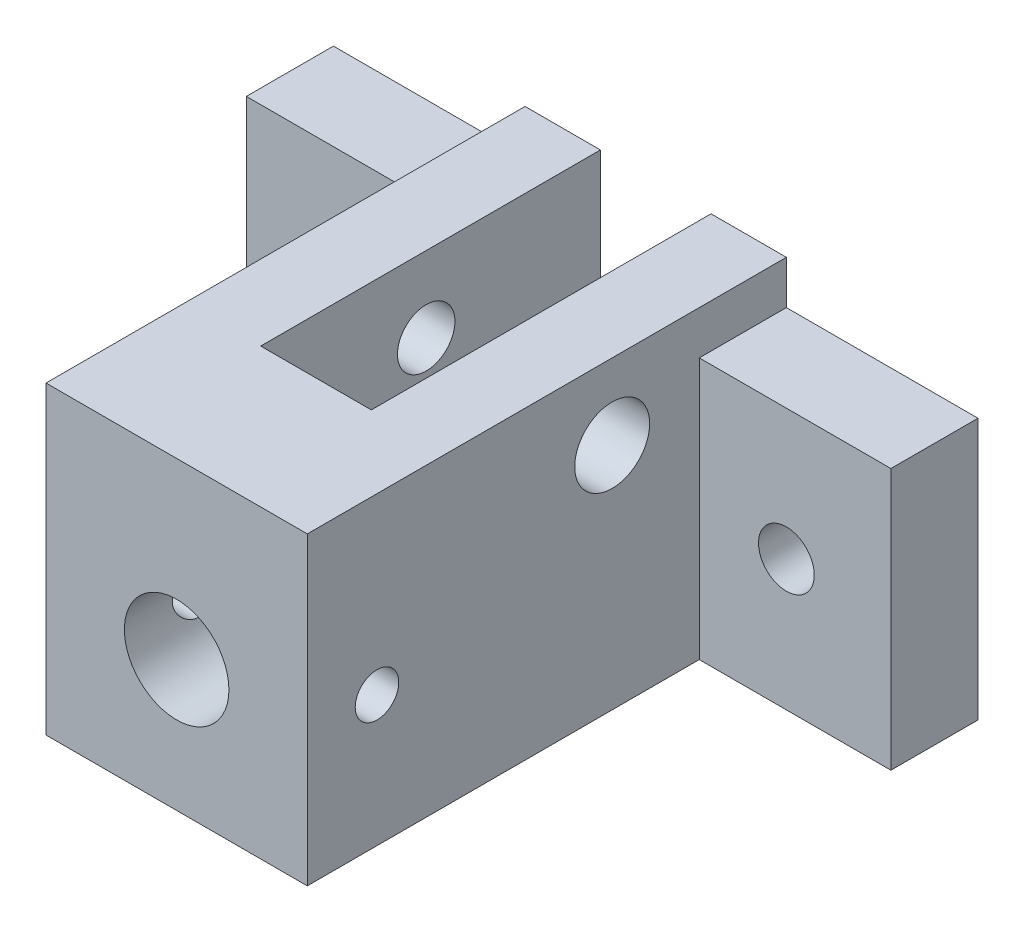
SolidWorks part; units mm, degrees
material "6061-T6 (SS)"
ref_plane "Front Plane" through (0, 0, 0) normal (0, 0, 1) x (1, 0, 0)
ref_plane "Top Plane" through (0, 0, 0) normal (0, 1, 0) x (1, 0, 0)
ref_plane "Right Plane" through (0, 0, 0) normal (1, 0, 0) x (0, 0, -1)
sketch "Sketch1" plane through (0, 0, 0) normal (0, 1, 0) x (1, 0, 0)
  line L0 (-7.5, 0) -> (7.5, 0)
  line L1 (7.5, 0) -> (7.5, 22.5)
  line L2 (7.5, 22.5) -> (18.5, 22.5)
  line L3 (18.5, 22.5) -> (18.5, 27.5)
  line L4 (18.5, 27.5) -> (3.175, 27.5)
  line L5 (3.175, 27.5) -> (3.175, 11.175)
  line L6 (3.175, 8) -> (0, 8)
  line L8 (-3.175, 27.5) -> (-3.175, 11.175)
  line L9 (-18.5, 27.5) -> (-3.175, 27.5)
  line L10 (-18.5, 22.5) -> (-18.5, 27.5)
  line L11 (-7.5, 22.5) -> (-18.5, 22.5)
  line L12 (-7.5, 0) -> (-7.5, 22.5)
  line L13 (12, 27.5) -> (12, 22.5) construction
  line L14 (-13, 27.5) -> (-13, 22.5) construction
  line L15 (-3.175, 11.175) -> (-3.175, 8)
  line L16 (0, 8) -> (-3.175, 8)
  line L17 (3.175, 11.175) -> (3.175, 8)
  arc A0 (-3.175, 11.175) -> (3.175, 11.175) centre (0, 11.175) ccw construction
  point P3 (0, 8)
  point P4 (0, 0)
  dimension "D1" = 5
  dimension "D2" = 6.35
  dimension "D3" = 11
  dimension "D4" = 25
  dimension "D5" = 27.5
  dimension "D6" = 37
  dimension "D7" = 8
extrude "Boss-Extrude1" add sketch "Sketch1" along normal mid plane 17.5
sketch "Sketch4" plane through (0, 0, 0) normal (0, 0, 1) x (1, 0, 0)
  line L0 (-7.5, -8.75) -> (7.5, -8.75) construction
  point P0 (0, -1.25)
  dimension "D1" = 7.5
hole_wizard "Ø6.0 (6) Diameter Hole1" positions "Sketch4" profile "Sketch5" hole size "Ø6.0" standard "ANSI Metric" end condition through all
sketch "Sketch5" plane through (0, -1.25, 0) normal (1, 0, 0) x (0, -1, 0)
  line L0 (0, 0) -> (0, 27.5)
  line L1 (0, 27.5) -> (3, 27.5)
  line L2 (3, 27.5) -> (3, 0)
  line L5 (3, 0) -> (0, 0)
  line L11 (0, -6.35) -> (0, 107.95) construction
  dimension "Thru Hole Dia." = 6
  dimension "Thru Hole Depth" = 27.5
sketch "Sketch2" plane through (0, 0, -22.5) normal (0, 0, 1) x (1, 0, 0)
  line L0 (7.5, -8.75) -> (18.5, -8.75) construction
  point P13 (12.5, -1.25)
  point P15 (-12.5, -1.25)
  dimension "D1" = 12.5
  dimension "D2" = 12.5
  dimension "D3" = 7.5
sketch "Sketch10" plane through (-7.5, 0, 0) normal (-1, 0, 0) x (0, 0, 1)
  line L0 (0, 8.75) -> (0, -8.75) construction
  point P0 (-4, -1.25)
  dimension "D1" = 4
hole_wizard "Tap Drill for M3x0.5 Tap1" positions "Sketch10" profile "Sketch11" hole size "M3x0.5" standard "ANSI Metric" end condition through all
sketch "Sketch11" plane through (-7.5, -1.25, -4) normal (0, 1, 0) x (0, 0, 1)
  line L0 (0, 0) -> (0, 26)
  line L1 (0, 26) -> (1.25, 26)
  line L2 (1.25, 26) -> (1.25, 0)
  line L5 (1.25, 0) -> (0, 0)
  line L11 (0, -6.35) -> (0, 107.95) construction
  dimension "Thru Hole Dia." = 2.5
  dimension "Thru Hole Depth" = 26
hole_wizard "M3 Clearance Hole1" positions "Sketch2" profile "Sketch3" hole size "M3" standard "ANSI Metric"
sketch "Sketch3" plane through (12.5, -1.25, -22.5) normal (1, 0, 0) x (0, -1, 0)
  line L0 (0, 0) -> (0, 5.9614)
  line L1 (0, 5.9614) -> (1.6, 5)
  line L2 (1.6, 5) -> (1.6, 0)
  line L5 (1.6, 0) -> (0, 0)
  line L10 (0, 5.9614) -> (-1.6, 5) construction
  line L11 (0, -6.35) -> (0, 107.95) construction
  dimension "Hole Dia." = 3.2
  dimension "Hole Depth" = 5
  dimension "Drill Angle" = 118
sketch "Sketch13" plane through (7.5, 0, 0) normal (1, 0, 0) x (0, 0, -1)
  line L0 (0, -8.75) -> (22.5, -8.75) construction
  circle A0 centre (17.5, 4.41) radius 2.125 construction
  point P4 (17.5, 4.41)
  dimension "D1" = 13.16
  dimension "D3" = 4.25
  dimension "D2" = 17.5
hole_wizard "M4 Clearance Hole1" positions "Sketch13" profile "Sketch17" hole size "M4" standard "ANSI Metric"
sketch "Sketch17" plane through (7.5, 4.41, -17.5) normal (0, 1, 0) x (0, 0, -1)
  line L0 (0, 0) -> (0, 5.6169)
  line L1 (0, 5.6169) -> (2.15, 4.325)
  line L2 (2.15, 4.325) -> (2.15, 0)
  line L5 (2.15, 0) -> (0, 0)
  line L10 (0, 5.6169) -> (-2.15, 4.325) construction
  line L11 (0, -6.35) -> (0, 107.95) construction
  dimension "Hole Dia." = 4.3
  dimension "Hole Depth" = 4.325
  dimension "Drill Angle" = 118
sketch "Sketch18" plane through (-3.175, 0, 0) normal (1, 0, 0) x (0, 0, -1)
  point P0 (17.5, 4.41)
hole_wizard "Tap Drill for M4x0.7 Tap1" positions "Sketch18" profile "Sketch19" hole size "M4x0.7" standard "ANSI Metric"
sketch "Sketch19" plane through (-3.175, 4.41, -17.5) normal (0, 1, 0) x (0, 0, -1)
  line L0 (0, 0) -> (0, 5.3164)
  line L1 (0, 5.3164) -> (1.65, 4.325)
  line L2 (1.65, 4.325) -> (1.65, 0)
  line L5 (1.65, 0) -> (0, 0)
  line L10 (0, 5.3164) -> (-1.65, 4.325) construction
  line L11 (0, -6.35) -> (0, 107.95) construction
  dimension "Hole Dia." = 3.3
  dimension "Hole Depth" = 4.325
  dimension "Drill Angle" = 118
sketch "Sketch16" plane through (0, 0, -22.5) normal (0, 0, 1) x (1, 0, 0)
  line L0 (-7.5, 8.75) -> (-7.5, -8.75) construction
  line L1 (-18.5, 8.75) -> (-7.5, 8.75)
  line L2 (-18.5, 8.75) -> (-18.5, 6.25)
  line L3 (-18.5, 6.25) -> (-7.5, 6.25)
  line L4 (-7.5, 8.75) -> (-7.5, 6.25)
  line L5 (-18.5, 8.75) -> (-7.5, 6.25) construction
  line L6 (-18.5, 6.25) -> (-7.5, 8.75) construction
  line L7 (7.5, 8.75) -> (7.5, -8.75) construction
  line L8 (7.5, 6.25) -> (18.5, 6.25)
  line L9 (7.5, 6.25) -> (7.5, 8.75)
  line L10 (7.5, 8.75) -> (18.5, 8.75)
  line L11 (18.5, 6.25) -> (18.5, 8.75)
  line L12 (7.5, 6.25) -> (18.5, 8.75) construction
  line L13 (7.5, 8.75) -> (18.5, 6.25) construction
  line L14 (-18.5, -8.75) -> (-7.5, -8.75) construction
  point P4 (-13, 7.5)
  point P12 (13, 7.5)
  dimension "D1" = 15
extrude "Cut-Extrude1" cut sketch "Sketch16" against normal through all both and the other way through all
